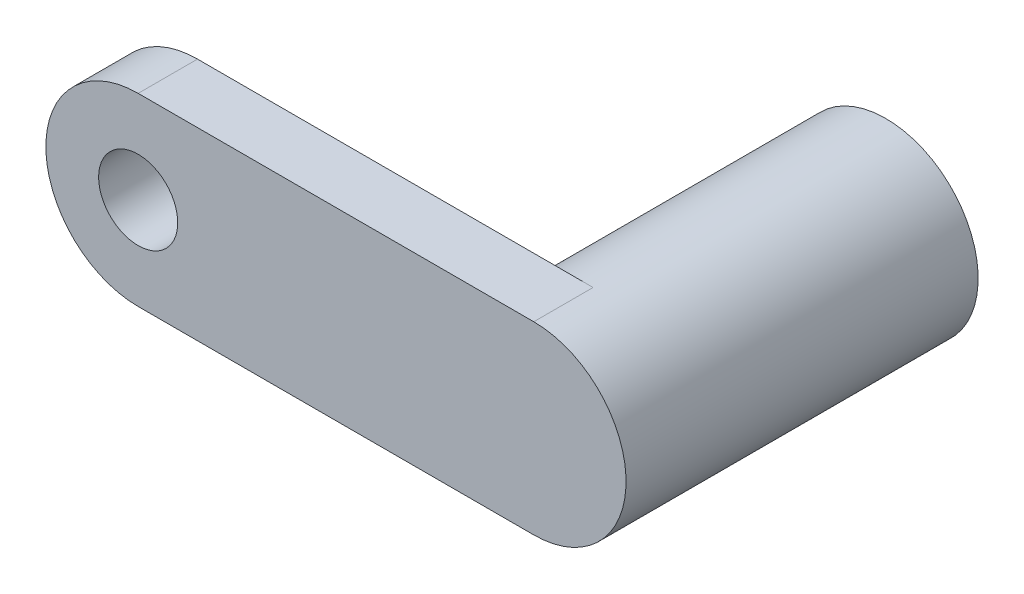
SolidWorks part; units mm, degrees
ref_plane "Plan de face" through (0, 0, 0) normal (0, 0, 1) x (1, 0, 0)
ref_plane "Plan de dessus" through (0, 0, 0) normal (0, 1, 0) x (1, 0, 0)
ref_plane "Plan de droite" through (0, 0, 0) normal (1, 0, 0) x (0, 0, -1)
ref_plane "Plan1" through (0, 0, 0) normal (0, 0, -1) x (-1, 0, 0)
sketch "Esquisse1" plane through (0, 0, 0) normal (0, 0, -1) x (-1, 0, 0)
  line L0 (0, 7) -> (-30, 7)
  line L1 (-30, -7) -> (0, -7)
  arc A0 (-30, 7) -> (-30, -7) centre (-30, 0) ccw
  arc A1 (0, -7) -> (0, 7) centre (0, 0) ccw
extrude "Boss.-Extru.1" add sketch "Esquisse1" against normal blind 4.5
sketch "Esquisse2" plane through (0, 0, 0) normal (0, 0, -1) x (-1, 0, 0)
  circle A0 centre (-30, 0) radius 7
extrude "Boss.-Extru.2" add sketch "Esquisse2" along normal blind 22.2
hole_wizard "Diamètre du perçage Ø4.2 (4.2)1" positions "Esquisse4" profile "Esquisse3" hole size "Ø4.2" standard "Ansi Metric"
sketch "Esquisse4" plane through (0, 0, -22.2) normal (0, 0, -1) x (-1, 0, 0)
  point P0 (-30, 0)
sketch "Esquisse3" plane through (30, 0, -22.2) normal (1, 0, 0) x (0, 1, 0)
  line L0 (0, 0) -> (0, 10)
  line L1 (0, 10) -> (2.1, 10)
  line L2 (2.1, 10) -> (2.1, 0)
  line L5 (2.1, 0) -> (0, 0)
  line L10 (0, 10) -> (-2.1, 10) construction
  line L11 (0, -6.35) -> (0, 107.95) construction
  dimension "Diamètre du perçage" = 4.2
  dimension "Profondeur du perçage" = 10
  dimension "Angle de pointe" = 180
hole_wizard "Diamètre du perçage Ø6.0 (6)1" positions "Esquisse6" profile "Esquisse5" hole size "Ø6.0" standard "Ansi Metric"
sketch "Esquisse6" plane through (0, 0, 0) normal (0, 0, -1) x (-1, 0, 0)
  point P0 (0, 0)
sketch "Esquisse5" plane through (0, 0, 0) normal (1, 0, 0) x (0, 1, 0)
  line L0 (0, 0) -> (0, 4.5)
  line L1 (0, 4.5) -> (3, 4.5)
  line L2 (3, 4.5) -> (3, 0)
  line L5 (3, 0) -> (0, 0)
  line L11 (0, -6.35) -> (0, 107.95) construction
  dimension "Diamètre du perçage jusqu'au prochain" = 6
  dimension "Profondeur du perçage jusqu'au prochain" = 4.5
